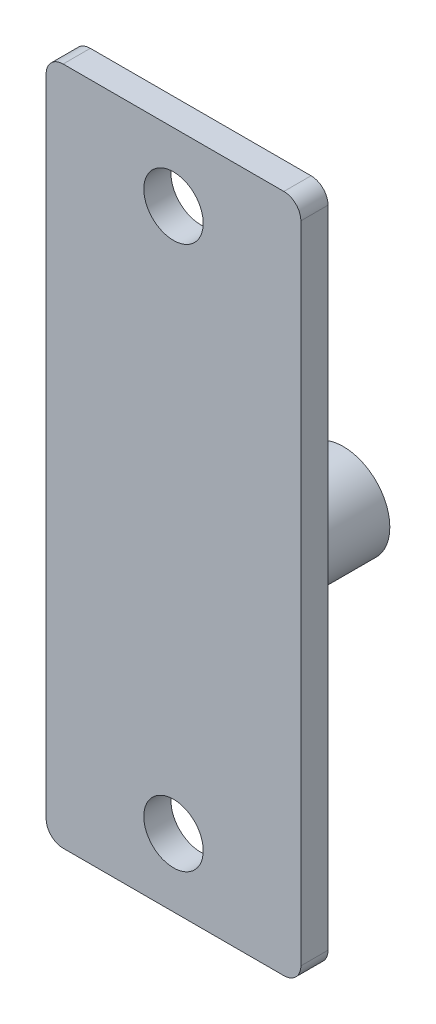
SolidWorks part; units mm, degrees
ref_plane "Front Plane" through (0, 0, 0) normal (0, 0, 1) x (1, 0, 0)
ref_plane "Top Plane" through (0, 0, 0) normal (0, 1, 0) x (1, 0, 0)
ref_plane "Right Plane" through (0, 0, 0) normal (1, 0, 0) x (0, 0, -1)
sketch "Sketch1" plane through (0, 0, 0) normal (0, 0, 1) x (1, 0, 0)
  line L0 (7.5, 4) -> (7.5, 0) construction
  line L1 (0, 0) -> (15, 0)
  line L2 (0, 0) -> (0, 40)
  line L3 (0, 40) -> (15, 40)
  line L4 (15, 0) -> (15, 40)
  line L5 (0, 20) -> (15, 20) construction
  circle A0 centre (7.5, 4) radius 1.75
  circle A1 centre (7.5, 36) radius 1.75
  circle A2 centre (7.5, 16) radius 2.7407 construction
  dimension "D1" = 3.5
  dimension "D2" = 4
  dimension "D3" = 40
  dimension "D5" = 16
  dimension "D6" = 5.4814
  dimension "D4" = 15
extrude "Boss-Extrude1" add sketch "Sketch1" along normal blind 1.6
fillet "Fillet1" radius 1 4 edges at (0, 40, 0.8) (15, 0, 0.8) (0, 0, 0.8) (15, 40, 0.8)
sketch "Sketch2" plane through (0, 0, 1.6) normal (0, 0, 1) x (1, 0, 0)
  circle A0 centre (7.5, 16) radius 2.7407 construction
  circle A1 centre (7.5, 16) radius 2.7407
extrude "Boss-Extrude2" add sketch "Sketch2" against normal blind 10
